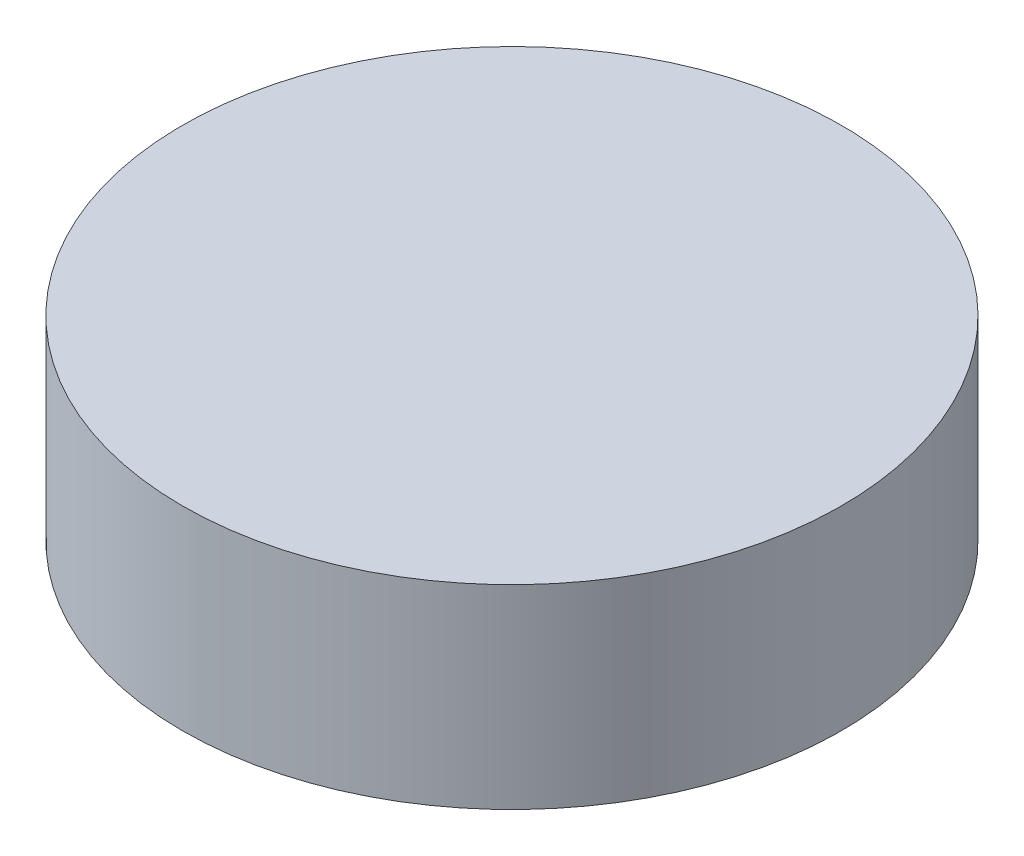
SolidWorks part; units mm, degrees
ref_plane "Front Plane" through (0, 0, 0) normal (0, 0, 1) x (1, 0, 0)
ref_plane "Top Plane" through (0, 0, 0) normal (0, 1, 0) x (1, 0, 0)
ref_plane "Right Plane" through (0, 0, 0) normal (1, 0, 0) x (0, 0, -1)
sketch "Sketch1" plane through (0, 0, 0) normal (0, 1, 0) x (1, 0, 0)
  circle A0 centre (0, 0) radius 139.7
  dimension "D1" = 279.4
extrude "Boss-Extrude1" add sketch "Sketch1" along normal blind 82.55
